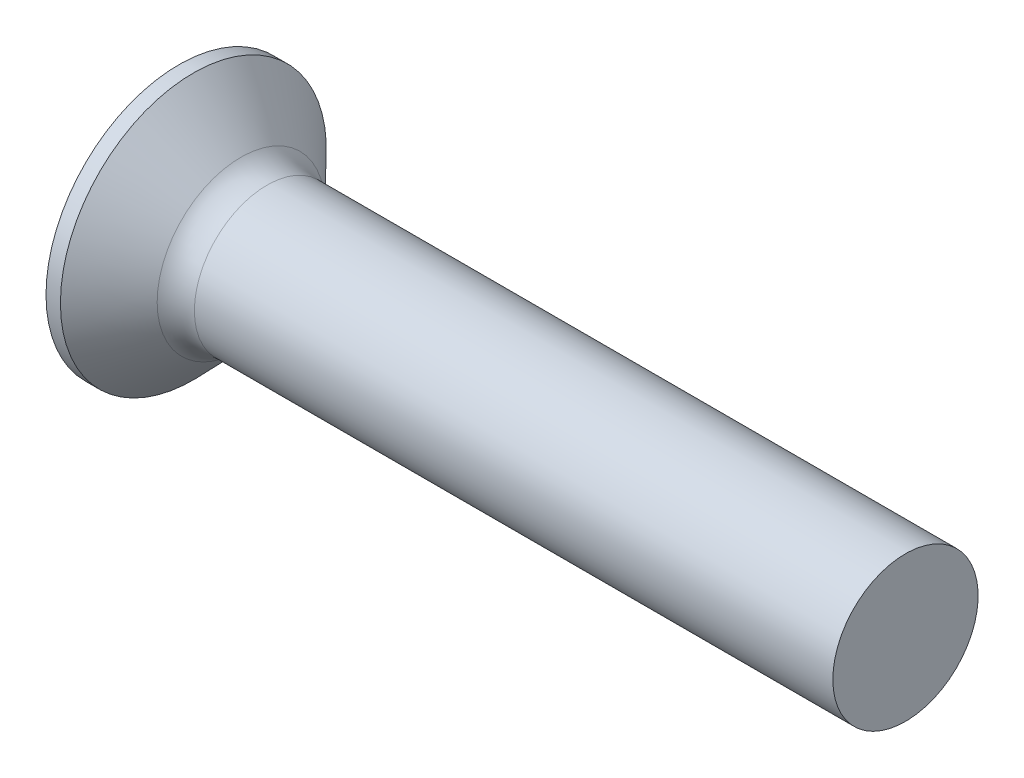
SolidWorks part; units mm, degrees
ref_plane "Plane1" through (0, 0, 0) normal (0, 0, 1) x (1, 0, 0)
ref_plane "Plane2" through (0, 0, 0) normal (0, 1, 0) x (1, 0, 0)
ref_plane "Plane3" through (0, 0, 0) normal (1, 0, 0) x (0, 0, -1)
sketch "BodySke" plane through (0, 0, 0) normal (0, 0, 1) x (1, 0, 0)
  line L0 (0, 0) -> (0, 9.15)
  line L1 (0, 9.15) -> (0.9924, 9.15)
  line L2 (5, 5) -> (50, 5)
  line L3 (50, 5) -> (50, 0)
  line L4 (50, 0) -> (0, 0)
  line L5 (-6.35, 0) -> (82.55, 0) construction
  line L6 (5, -5) -> (50, -5) construction
  line L7 (0.9924, -9.15) -> (5, -5) construction
  line L8 (0.9924, 9.15) -> (5, 5)
  line L9 (0, -9.15) -> (0.9924, -9.15) construction
  line L10 (6.5, 6.5875) -> (6.5, -2.9375) construction
  line L11 (0, 6.35) -> (0, -3.175) construction
  dimension "Diameter" = 10
  dimension "Length" = 50
  dimension "Head_ht" = 5
  dimension "Head_dia" = 18.3
  dimension "Head_ang" = 92
  dimension "D6" = 0.9924
  dimension "Advance" = 1.5
  dimension "Thread_nom" = 50
revolve "Base-Revolve" add sketch "BodySke" angle 360 about L5
cosmetic thread "ThreadCosmetic" parameters "Thread_length"=43.5, "Thread_minor"=7.9248
fillet "Fillet1" radius 2.5 1 edges at (5, 0, 5)
sketch "Sketch3" plane through (0, 0, 0) normal (-1, 0, 0) x (0, 0, 1)
  line L0 (-1.08, 4.9) -> (1.08, 4.9)
  line L1 (1.08, 4.9) -> (1.08, -4.9)
  line L2 (1.08, -4.9) -> (-1.08, -4.9)
  line L3 (-1.08, -4.9) -> (-1.08, 4.9)
  dimension "D1" = 4.9
  dimension "Cross_dia" = 9.8
  dimension "D2" = 1.08
  dimension "Cross_width" = 2.16
ref_plane "Plane4" through (5.64, 0, 0) normal (-1, 0, 0) x (0, 0, 1)
sketch "Sketch4" plane through (5.64, 0, 0) normal (-1, 0, 0) x (0, 0, 1)
  line L0 (-1.08, 2.088) -> (1.08, 2.088)
  line L3 (1.08, 2.088) -> (1.08, -2.088)
  line L4 (1.08, -2.088) -> (-1.08, -2.088)
  line L5 (-1.08, -2.088) -> (-1.08, 2.088)
  dimension "D1" = 2.16
  dimension "D2" = 4.176
  dimension "D3" = 1.08
  dimension "D4" = 2.088
loft "Recess" cut profiles "Sketch3", "Sketch4"
pattern_circular "RecPat" count 2 every 90 about axis through (0, 0, 0) along (1, 0, 0) of "Recess"
sketch "RecCorSke" plane through (0, 0, 0) normal (0, 0, 1) x (1, 0, 0)
  line L0 (-3.175, 0) -> (15.875, 0) construction
  line L2 (0, 0) -> (0, 2.3249)
  line L3 (0, 2.3249) -> (5.64, 1.9305)
  line L4 (5.64, 1.9305) -> (6.2673, 0)
  line L5 (6.2673, 0) -> (0, 0)
  dimension "Diameter" = 3.861
  dimension "Depth" = 5.64
  dimension "Draft_angle" = 4
  dimension "Bottom_angle" = 18
revolve "RecessCore" cut sketch "RecCorSke" angle 360 about L0
sketch "ThdSchSke" plane through (0, 0, 0) normal (0, 0, 1) x (1, 0, 0)
  line L0 (6.5, -3.9624) -> (5.7735, -5)
  line L1 (6.5, -3.9624) -> (7.2265, -5)
  line L2 (7.2265, -5) -> (7.2265, -6.25)
  line L3 (-3.175, 0) -> (5.1513, 0) construction
  line L5 (7.2265, -6.25) -> (5.7735, -6.25)
  line L6 (5.7735, -6.25) -> (5.7735, -5)
  line L7 (0, 9.15) -> (0, -9.15) construction
  dimension "Thread_minor" = 7.9248
  dimension "Diameter" = 10
  dimension "Start" = 6.5
  dimension "SideAngle" = 55
  dimension "VeeAngle" = 70
  dimension "Overcut" = 12.5
revolve "ThreadSchematic" [suppressed] cut sketch "ThdSchSke" angle 360 about L3
pattern_linear "ThdSchPat" [suppressed]
equation "\"D1@Sketch3\" = \"Cross_dia@Sketch3\" / 2"
equation "\"D2@Sketch3\" = \"Cross_width@Sketch3\" / 2"
equation "\"Depth@RecCorSke\" = \"Cross_depth@Plane4\""
equation "\"D1@Sketch4\" = \"Cross_width@Sketch3\""
equation "\"D2@Sketch4\" = \"Cross_dia@Sketch3\" - 2.0 * \"Cross_depth@Plane4\" * tan(26.5  * 0.017453292)"
equation "\"D3@Sketch4\" = \"D1@Sketch4\" / 2"
equation "\"D4@Sketch4\" = \"D2@Sketch4\" / 2"
equation "\"Thread_length@ThreadCosmetic\" = ((sgn( (\"Length@BodySke\" - \"Advance@BodySke\" * 1.0 - \"Head_ht@BodySke\" ) - \"Thread_nom@BodySke\" )-1)*( (\"Length@BodySke\" - \"Advance@BodySke\" * 1.0 - \"Head_ht@BodySke\" ) - \"Thread_nom@BodySke\" ))/-2+ \"Thread_nom@BodySke\""
equation "\"Thread_minor@ThdSchSke\" = \"Thread_minor@ThreadCosmetic\""
equation "\"Diameter@ThdSchSke\" = \"Diameter@BodySke\""
equation "\"Overcut@ThdSchSke\" = \"Diameter@BodySke\" * 1.25"
equation "\"Start@ThdSchSke\" = 0.000001 + \"Length@BodySke\" - \"Thread_length@ThreadCosmetic\"  '---Countersunk---"
equation "\"Num_threads@ThdSchPat\" = int( \"Thread_length@ThreadCosmetic\" / \"Advance@BodySke\" + 0.999 )  + 1"
equation "\"Advance@ThdSchPat\" = \"Thread_length@ThreadCosmetic\" /  (\"Num_threads@ThdSchPat\" - 1) 'relax it"
